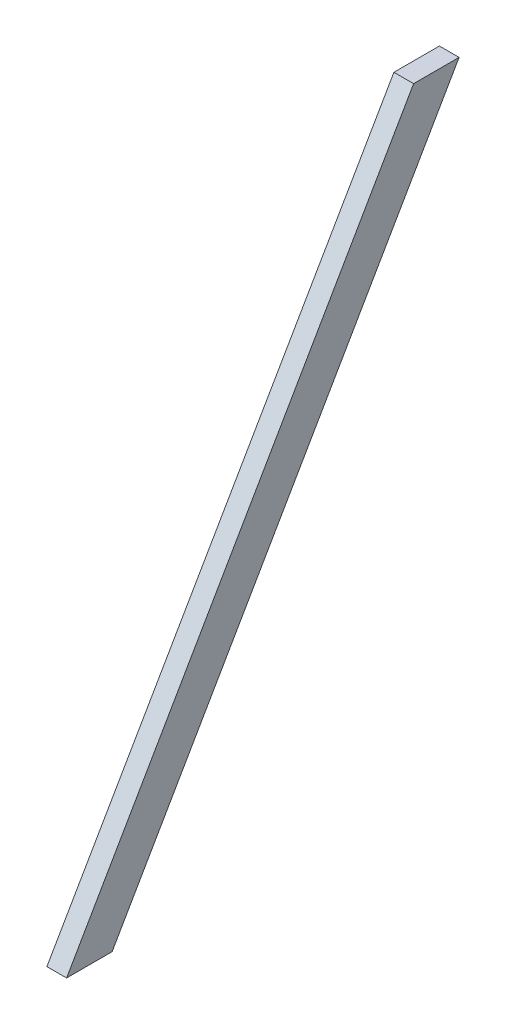
SolidWorks part; units mm, degrees
ref_plane "Front Plane" through (0, 0, 0) normal (0, 0, 1) x (1, 0, 0)
ref_plane "Top Plane" through (0, 0, 0) normal (0, 1, 0) x (1, 0, 0)
ref_plane "Right Plane" through (0, 0, 0) normal (1, 0, 0) x (0, 0, -1)
sketch "Sketch1" plane through (0, 0, 0) normal (1, 0, 0) x (0, 0, -1)
  line L0 (0, 0) -> (-58.6588, 0)
  line L1 (-58.6588, 0) -> (388.6352, 774.7359)
  line L2 (388.6352, 774.7359) -> (447.294, 774.7359)
  line L3 (447.294, 774.7359) -> (0, 0)
  line L4 (0, 0) -> (-43.9941, 25.4) construction
  line L5 (0, 0) -> (793.4679, 0) construction
  dimension "D1" = 50.8
  dimension "D2" = 894.588
  dimension "D3" = 60
extrude "Boss-Extrude1" add sketch "Sketch1" along normal blind 25.4
